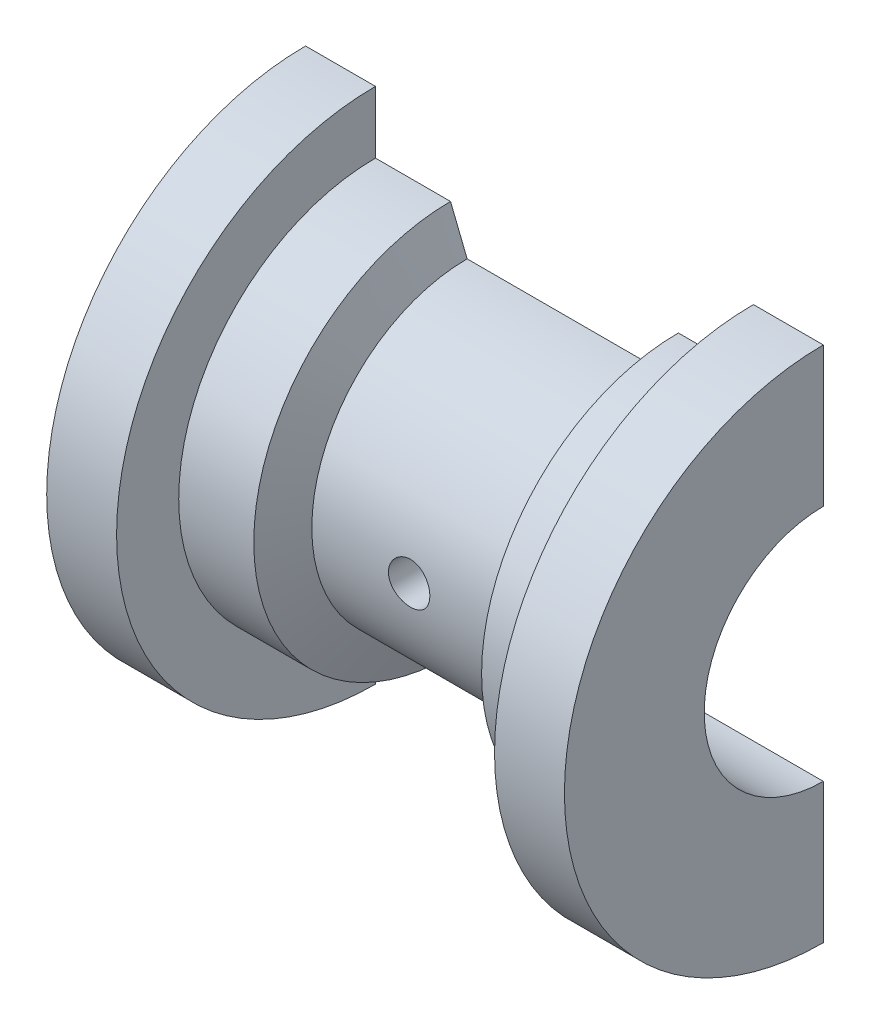
SolidWorks part; units mm, degrees
ref_plane "Front Plane" through (0, 0, 0) normal (0, 0, 1) x (1, 0, 0)
ref_plane "Top Plane" through (0, 0, 0) normal (0, 1, 0) x (1, 0, 0)
ref_plane "Right Plane" through (0, 0, 0) normal (1, 0, 0) x (0, 0, -1)
sketch "Sketch1" plane through (0, 0, 0) normal (0, 0, 1) x (1, 0, 0)
  line L0 (-19.8823, 25) -> (-19.8823, 11.5)
  line L1 (-19.8823, 11.5) -> (30.1177, 11.5)
  line L2 (30.1177, 11.5) -> (30.1177, 25)
  line L3 (30.1177, 25) -> (23.3677, 25)
  line L4 (23.3677, 25) -> (23.3677, 19)
  line L5 (23.3677, 19) -> (16.1177, 19)
  line L7 (14.5126, 15) -> (-4.2773, 15)
  line L9 (-5.8823, 19) -> (-13.1323, 19)
  line L10 (-13.1323, 19) -> (-13.1323, 25)
  line L11 (-13.1323, 25) -> (-19.8823, 25)
  line L12 (-47.288, 0) -> (41.0246, 0) construction
  line L13 (-5.8823, 19) -> (-4.2773, 15)
  line L14 (16.1177, 19) -> (14.5126, 15)
  line L15 (5.1177, 15) -> (5.1177, 0) construction
  dimension "D1" = 25
  dimension "D2" = 11.5
  dimension "D3" = 22
  dimension "D4" = 36.5
  dimension "D5" = 6.75
  dimension "D6" = 6.75
  dimension "D7" = 19
  dimension "D8" = 15
  dimension "D9" = 5.1177
revolve "Revolve1" add sketch "Sketch1" angle 180 about L12
sketch "Sketch3" plane through (0, 0, 0) normal (0, 1, 0) x (1, 0, 0)
  line L0 (5.1177, 0) -> (5.1177, -16.9259) construction
  line L1 (14.5126, 0) -> (-4.2773, 0) construction
  line L2 (3.1177, -15) -> (3.1177, 0)
  line L3 (-4.2773, -15) -> (14.5126, -15) construction
  line L4 (5.1177, -15) -> (5.1177, 0)
  line L5 (3.1177, 0) -> (5.1177, 0)
  line L6 (5.1177, -15) -> (3.1177, -15)
  dimension "D1" = 2
revolve "Cut-Revolve1" cut sketch "Sketch3" angle 360 about L0
